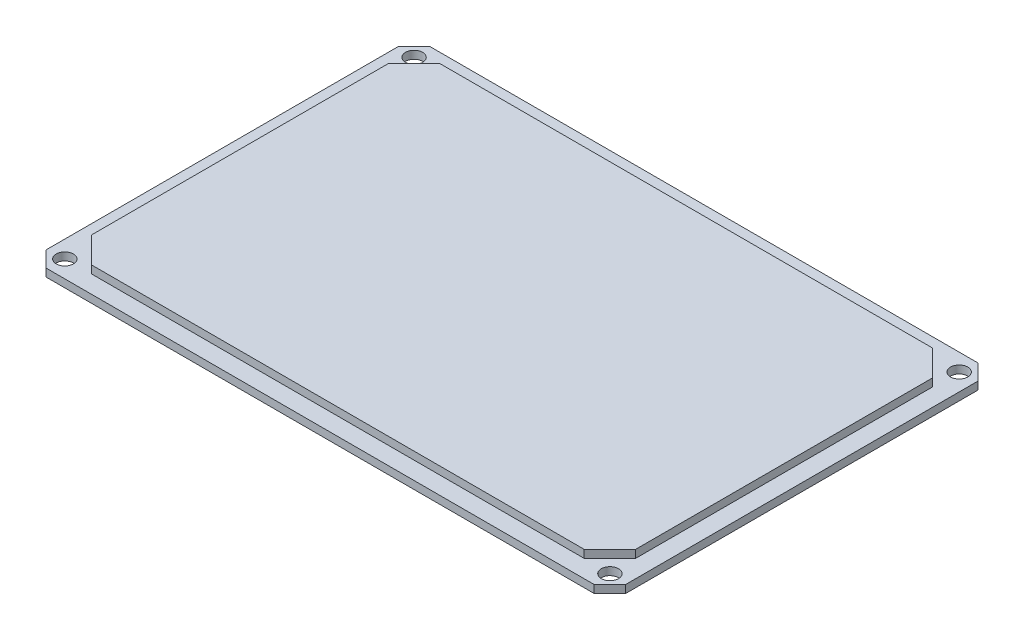
SolidWorks part; units mm, degrees
ref_plane "Front Plane" through (0, 0, 0) normal (0, 0, 1) x (1, 0, 0)
ref_plane "Top Plane" through (0, 0, 0) normal (0, 1, 0) x (1, 0, 0)
ref_plane "Right Plane" through (0, 0, 0) normal (1, 0, 0) x (0, 0, -1)
sketch "Sketch1" plane through (0, 0, 0) normal (0, 1, 0) x (1, 0, 0)
  line L1 (-37, -24.5) -> (37, -24.5)
  line L2 (-37, -24.5) -> (-37, 24.5)
  line L3 (-37, 24.5) -> (37, 24.5)
  line L4 (37, -24.5) -> (37, 24.5)
  line L5 (-37, -24.5) -> (37, 24.5) construction
  line L6 (-37, 24.5) -> (37, -24.5) construction
  point P0 (0, 0)
  dimension "D1" = 74
  dimension "D2" = 49
extrude "Boss-Extrude1" add sketch "Sketch1" along normal blind 1
sketch "Sketch2" plane through (0, 1, 0) normal (0, 1, 0) x (1, 0, 0)
  line L1 (-34.75, -22.25) -> (34.75, -22.25)
  line L2 (-34.75, -22.25) -> (-34.75, 22.25)
  line L3 (-34.75, 22.25) -> (34.75, 22.25)
  line L4 (34.75, -22.25) -> (34.75, 22.25)
  line L5 (-34.75, -22.25) -> (34.75, 22.25) construction
  line L6 (-34.75, 22.25) -> (34.75, -22.25) construction
  point P0 (0, 0)
  dimension "D1" = 69.5
  dimension "D2" = 44.5
extrude "Boss-Extrude2" add sketch "Sketch2" along normal blind 1
chamfer "Chamfer1" distance 2 angle 45 4 edges at (-37, 0.5, -24.5) (37, 0.5, -24.5) (37, 0.5, 24.5) (-37, 0.5, 24.5)
chamfer "Chamfer2" distance 3.3 angle 45 4 edges at (34.75, 1.5, 22.25) (-34.75, 1.5, 22.25) (-34.75, 1.5, -22.25) (34.75, 1.5, -22.25)
sketch "Sketch3" plane through (0, 1, 0) normal (0, 1, 0) x (1, 0, 0)
  line L0 (35, 24.5) -> (-35, 24.5) construction
  line L1 (-37, 22.5) -> (-37, -22.5) construction
  line L2 (37, -22.5) -> (37, 22.5) construction
  line L3 (-35, -24.5) -> (35, -24.5) construction
  circle A0 centre (-34.8, 22.3) radius 1.1
  circle A1 centre (34.8, 22.3) radius 1.1
  circle A2 centre (34.8, -22.3) radius 1.1
  circle A3 centre (-34.8, -22.3) radius 1.1
  dimension "D1" = 2.2
  dimension "D2" = 2.2
  dimension "D3" = 2.2
  dimension "D4" = 2.2
  dimension "D5" = 2.2
  dimension "D6" = 2.2
  dimension "D7" = 2.2
  dimension "D8" = 2.2
extrude "Cut-Extrude1" cut sketch "Sketch3" against normal blind 1
